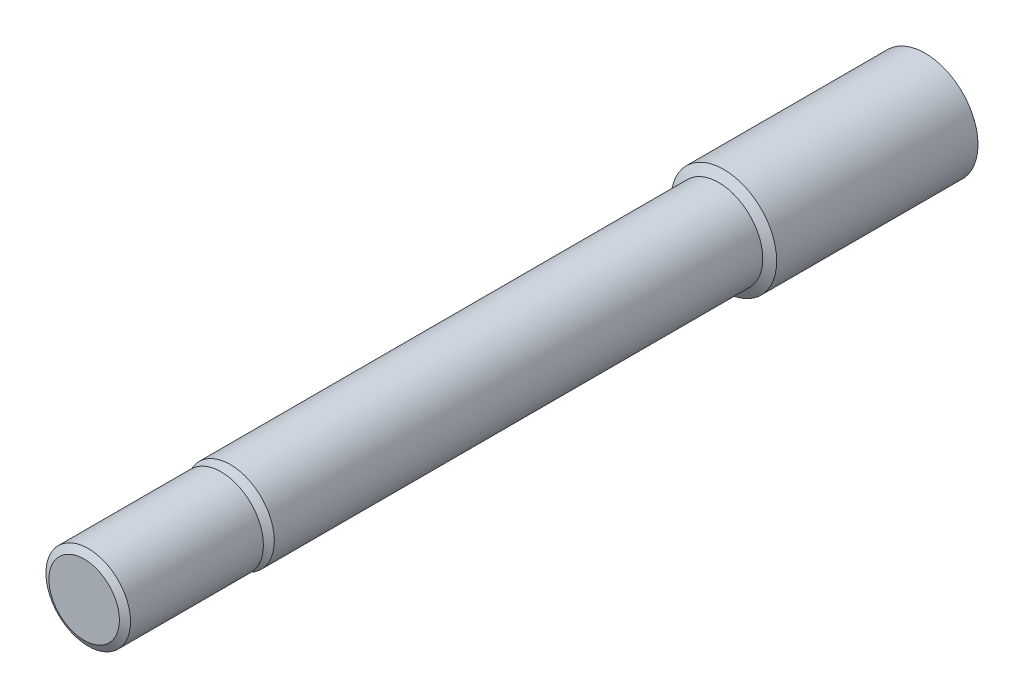
SolidWorks part; units mm, degrees
material "AISI 1010 Steel, hot rolled bar"
ref_plane "Front" through (0, 0, 0) normal (0, 0, 1) x (1, 0, 0)
ref_plane "Top" through (0, 0, 0) normal (0, 1, 0) x (1, 0, 0)
ref_plane "Right" through (0, 0, 0) normal (1, 0, 0) x (0, 0, -1)
sketch "Sketch2" plane through (0, 0, 0) normal (1, 0, 0) x (0, 0, -1)
  line L0 (0, 0) -> (27.164, 0) construction
  line L1 (0, 0) -> (0, 1)
  line L2 (0.1155, 1.2) -> (3.8845, 1.2)
  line L3 (3.8845, 1.2) -> (4, 1)
  line L4 (4, 1) -> (4.1443, 1.25)
  line L5 (4.1443, 1.25) -> (18, 1.25)
  line L6 (18, 1.25) -> (18.1443, 1.5)
  line L7 (18.1443, 1.5) -> (23.8557, 1.5)
  line L8 (23.8557, 1.5) -> (24, 1.25)
  line L9 (24, 1.25) -> (24, 0)
  line L10 (24, 0) -> (0, 0)
  line L11 (0.1155, 1.2) -> (0, 1)
  dimension "D1" = 2.4
  dimension "D2" = 3
  dimension "D3" = 24
  dimension "D4" = 6
  dimension "D5" = 60
  dimension "D6" = 30
  dimension "D7" = 2.5
  dimension "D8" = 4
  dimension "D9" = 60
  dimension "D10" = 2
  dimension "D11" = 60
revolve "Revolve1" add sketch "Sketch2" angle 360 about L0
cosmetic thread "Cosmetic Thread1" parameters "D1"=5, "D2"=2.439
cosmetic thread "Cosmetic Thread2" parameters "D1"=4, "D2"=1.693
